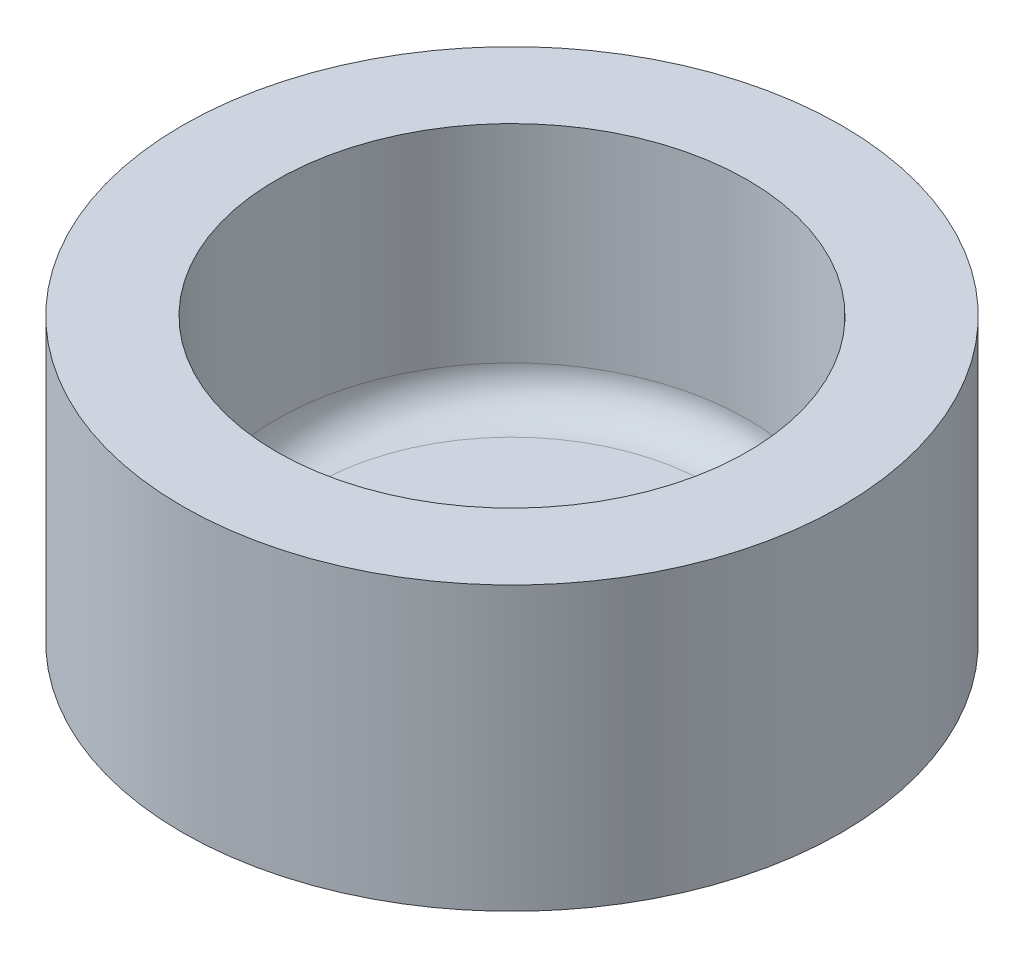
SolidWorks part; units mm, degrees
ref_plane "Front Plane" through (0, 0, 0) normal (0, 0, 1) x (1, 0, 0)
ref_plane "Top Plane" through (0, 0, 0) normal (0, 1, 0) x (1, 0, 0)
ref_plane "Right Plane" through (0, 0, 0) normal (1, 0, 0) x (0, 0, -1)
sketch "Sketch1" plane through (0, 0, 0) normal (0, 1, 0) x (1, 0, 0)
  circle A0 centre (0, 0) radius 17.5
  circle A1 centre (0, 0) radius 12.5
  dimension "D1" = 5
  dimension "D2" = 25
extrude "Boss-Extrude1" add sketch "Sketch1" along normal blind 15
sketch "Sketch2" plane through (0, 0, 0) normal (0, -1, 0) x (1, 0, 0)
  circle A0 centre (0, 0) radius 12.5 construction
  circle A1 centre (0, 0) radius 12.5
extrude "Boss-Extrude2" add sketch "Sketch2" against normal blind 2
fillet "Fillet1" radius 2 1 edges at (0, 2, -12.5)
sketch "Sketch5" plane through (0, 2, 0) normal (0, 1, 0) x (1, 0, 0)
  line L0 (0, 0) -> (0, 24.5) construction
  line L1 (0, 2.5) -> (0, 4.5) construction
  circle A6 centre (0, 0) radius 2.5 construction
  circle A7 centre (0, 0) radius 4.5 construction
  circle A8 centre (0, 0) radius 6.5 construction
  circle A9 centre (0, 0) radius 8.5 construction
  circle A10 centre (0, 0) radius 10.5 construction
  circle A11 centre (0, 0) radius 12.5 construction
  circle A12 centre (0, 0) radius 14.5 construction
  circle A13 centre (0, 0) radius 16.5 construction
  circle A14 centre (0, 0) radius 18.5 construction
  circle A15 centre (0, 0) radius 20.5 construction
  circle A16 centre (0, 0) radius 22.5 construction
  circle A17 centre (0, 0) radius 24.5 construction
  circle A18 centre (0, 2.5) radius 0.5
  circle A20 centre (0, 4.5) radius 0.5
  circle A21 centre (0, 6.5) radius 0.5
  circle A22 centre (0, 8.5) radius 0.5
  circle A23 centre (0, 10.5) radius 0.5
  circle A24 centre (0, 12.5) radius 0.5
  circle A25 centre (0, 14.5) radius 0.5
  circle A26 centre (0, 16.5) radius 0.5
  circle A31 centre (1.7678, 1.7678) radius 0.5
  circle A32 centre (2.5, 0) radius 0.5
  circle A33 centre (1.7678, -1.7678) radius 0.5
  circle A34 centre (0, -2.5) radius 0.5
  circle A35 centre (-1.7678, -1.7678) radius 0.5
  circle A36 centre (-2.5, 0) radius 0.5
  circle A37 centre (-1.7678, 1.7678) radius 0.5
  circle A38 centre (1.9525, 4.0544) radius 0.5
  circle A39 centre (3.5182, 2.8057) radius 0.5
  circle A40 centre (4.3872, 1.0013) radius 0.5
  circle A41 centre (4.3872, -1.0013) radius 0.5
  circle A42 centre (3.5182, -2.8057) radius 0.5
  circle A43 centre (1.9525, -4.0544) radius 0.5
  circle A44 centre (0, -4.5) radius 0.5
  circle A45 centre (-1.9525, -4.0544) radius 0.5
  circle A46 centre (-3.5182, -2.8057) radius 0.5
  circle A47 centre (-4.3872, -1.0013) radius 0.5
  circle A48 centre (-4.3872, 1.0013) radius 0.5
  circle A49 centre (-3.5182, 2.8057) radius 0.5
  circle A50 centre (-1.9525, 4.0544) radius 0.5
  circle A51 centre (1.9159, 6.2112) radius 0.5
  circle A52 centre (3.6616, 5.3706) radius 0.5
  circle A53 centre (5.0819, 4.0527) radius 0.5
  circle A54 centre (6.0507, 2.3747) radius 0.5
  circle A55 centre (6.4818, 0.4857) radius 0.5
  circle A56 centre (6.337, -1.4464) radius 0.5
  circle A57 centre (5.6292, -3.25) radius 0.5
  circle A58 centre (4.4211, -4.7648) radius 0.5
  circle A59 centre (2.8202, -5.8563) radius 0.5
  circle A60 centre (0.9688, -6.4274) radius 0.5
  circle A61 centre (-0.9688, -6.4274) radius 0.5
  circle A62 centre (-2.8202, -5.8563) radius 0.5
  circle A63 centre (-4.4211, -4.7648) radius 0.5
  circle A64 centre (-5.6292, -3.25) radius 0.5
  circle A65 centre (-6.337, -1.4464) radius 0.5
  circle A66 centre (-6.4818, 0.4857) radius 0.5
  circle A67 centre (-6.0507, 2.3747) radius 0.5
  circle A68 centre (-5.0819, 4.0527) radius 0.5
  circle A69 centre (-3.6616, 5.3706) radius 0.5
  circle A70 centre (-1.9159, 6.2112) radius 0.5
  circle A71 centre (1.8914, 8.2869) radius 0.5
  circle A72 centre (3.688, 7.6582) radius 0.5
  circle A73 centre (5.2997, 6.6456) radius 0.5
  circle A74 centre (6.6456, 5.2997) radius 0.5
  circle A75 centre (7.6582, 3.688) radius 0.5
  circle A76 centre (8.2869, 1.8914) radius 0.5
  circle A77 centre (8.5, 0) radius 0.5
  circle A78 centre (8.2869, -1.8914) radius 0.5
  circle A79 centre (7.6582, -3.688) radius 0.5
  circle A80 centre (6.6456, -5.2997) radius 0.5
  circle A81 centre (5.2997, -6.6456) radius 0.5
  circle A82 centre (3.688, -7.6582) radius 0.5
  circle A83 centre (1.8914, -8.2869) radius 0.5
  circle A84 centre (0, -8.5) radius 0.5
  circle A85 centre (-1.8914, -8.2869) radius 0.5
  circle A86 centre (-3.688, -7.6582) radius 0.5
  circle A87 centre (-5.2997, -6.6456) radius 0.5
  circle A88 centre (-6.6456, -5.2997) radius 0.5
  circle A89 centre (-7.6582, -3.688) radius 0.5
  circle A90 centre (-8.2869, -1.8914) radius 0.5
  circle A91 centre (-8.5, 0) radius 0.5
  circle A92 centre (-8.2869, 1.8914) radius 0.5
  circle A93 centre (-7.6582, 3.688) radius 0.5
  circle A94 centre (-6.6456, 5.2997) radius 0.5
  circle A95 centre (-5.2997, 6.6456) radius 0.5
  circle A96 centre (-3.688, 7.6582) radius 0.5
  circle A97 centre (-1.8914, 8.2869) radius 0.5
  circle A98 centre (1.8233, 10.3405) radius 0.5
  circle A99 centre (3.5912, 9.8668) radius 0.5
  circle A100 centre (5.25, 9.0933) radius 0.5
  circle A101 centre (6.7493, 8.0435) radius 0.5
  circle A102 centre (8.0435, 6.7493) radius 0.5
  circle A103 centre (9.0933, 5.25) radius 0.5
  circle A104 centre (9.8668, 3.5912) radius 0.5
  circle A105 centre (10.3405, 1.8233) radius 0.5
  circle A106 centre (10.5, 0) radius 0.5
  circle A107 centre (10.3405, -1.8233) radius 0.5
  circle A108 centre (9.8668, -3.5912) radius 0.5
  circle A109 centre (9.0933, -5.25) radius 0.5
  circle A110 centre (8.0435, -6.7493) radius 0.5
  circle A111 centre (6.7493, -8.0435) radius 0.5
  circle A112 centre (5.25, -9.0933) radius 0.5
  circle A113 centre (3.5912, -9.8668) radius 0.5
  circle A114 centre (1.8233, -10.3405) radius 0.5
  circle A115 centre (0, -10.5) radius 0.5
  circle A116 centre (-1.8233, -10.3405) radius 0.5
  circle A117 centre (-3.5912, -9.8668) radius 0.5
  circle A118 centre (-5.25, -9.0933) radius 0.5
  circle A119 centre (-6.7493, -8.0435) radius 0.5
  circle A120 centre (-8.0435, -6.7493) radius 0.5
  circle A121 centre (-9.0933, -5.25) radius 0.5
  circle A122 centre (-9.8668, -3.5912) radius 0.5
  circle A123 centre (-10.3405, -1.8233) radius 0.5
  circle A124 centre (-10.5, 0) radius 0.5
  circle A125 centre (-10.3405, 1.8233) radius 0.5
  circle A126 centre (-9.8668, 3.5912) radius 0.5
  circle A127 centre (-9.0933, 5.25) radius 0.5
  circle A128 centre (-8.0435, 6.7493) radius 0.5
  circle A129 centre (-6.7493, 8.0435) radius 0.5
  circle A130 centre (-5.25, 9.0933) radius 0.5
  circle A131 centre (-3.5912, 9.8668) radius 0.5
  circle A132 centre (-1.8233, 10.3405) radius 0.5
  circle A133 centre (1.863, 12.3604) radius 0.5
  circle A134 centre (3.6844, 11.9447) radius 0.5
  circle A135 centre (5.4235, 11.2621) radius 0.5
  circle A136 centre (7.0415, 10.328) radius 0.5
  circle A137 centre (8.5022, 9.1631) radius 0.5
  circle A138 centre (9.7729, 7.7936) radius 0.5
  circle A139 centre (10.8253, 6.25) radius 0.5
  circle A140 centre (11.6359, 4.5668) radius 0.5
  circle A141 centre (12.1866, 2.7815) radius 0.5
  circle A142 centre (12.465, 0.9341) radius 0.5
  circle A143 centre (12.465, -0.9341) radius 0.5
  circle A144 centre (12.1866, -2.7815) radius 0.5
  circle A145 centre (11.6359, -4.5668) radius 0.5
  circle A146 centre (10.8253, -6.25) radius 0.5
  circle A147 centre (9.7729, -7.7936) radius 0.5
  circle A148 centre (8.5022, -9.1631) radius 0.5
  circle A149 centre (7.0415, -10.328) radius 0.5
  circle A150 centre (5.4235, -11.2621) radius 0.5
  circle A151 centre (3.6844, -11.9447) radius 0.5
  circle A152 centre (1.863, -12.3604) radius 0.5
  circle A153 centre (0, -12.5) radius 0.5
  circle A154 centre (-1.863, -12.3604) radius 0.5
  circle A155 centre (-3.6844, -11.9447) radius 0.5
  circle A156 centre (-5.4235, -11.2621) radius 0.5
  circle A157 centre (-7.0415, -10.328) radius 0.5
  circle A158 centre (-8.5022, -9.1631) radius 0.5
  circle A159 centre (-9.7729, -7.7936) radius 0.5
  circle A160 centre (-10.8253, -6.25) radius 0.5
  circle A161 centre (-11.6359, -4.5668) radius 0.5
  circle A162 centre (-12.1866, -2.7815) radius 0.5
  circle A163 centre (-12.465, -0.9341) radius 0.5
  circle A164 centre (-12.465, 0.9341) radius 0.5
  circle A165 centre (-12.1866, 2.7815) radius 0.5
  circle A166 centre (-11.6359, 4.5668) radius 0.5
  circle A167 centre (-10.8253, 6.25) radius 0.5
  circle A168 centre (-9.7729, 7.7936) radius 0.5
  circle A169 centre (-8.5022, 9.1631) radius 0.5
  circle A170 centre (-7.0415, 10.328) radius 0.5
  circle A171 centre (-5.4235, 11.2621) radius 0.5
  circle A172 centre (-3.6844, 11.9447) radius 0.5
  circle A173 centre (-1.863, 12.3604) radius 0.5
  circle A174 centre (1.8542, 14.381) radius 0.5
  circle A175 centre (3.678, 14.0258) radius 0.5
  circle A176 centre (5.4414, 13.4403) radius 0.5
  circle A177 centre (7.1154, 12.6341) radius 0.5
  circle A178 centre (8.6726, 11.6205) radius 0.5
  circle A179 centre (10.0874, 10.4161) radius 0.5
  circle A180 centre (11.3366, 9.0406) radius 0.5
  circle A181 centre (12.3996, 7.5167) radius 0.5
  circle A182 centre (13.259, 5.8694) radius 0.5
  circle A183 centre (13.9007, 4.1257) radius 0.5
  circle A184 centre (14.3141, 2.3142) radius 0.5
  circle A185 centre (14.4926, 0.4647) radius 0.5
  circle A186 centre (14.433, -1.3923) radius 0.5
  circle A187 centre (14.1365, -3.2266) radius 0.5
  circle A188 centre (13.6078, -5.0078) radius 0.5
  circle A189 centre (12.8557, -6.7068) radius 0.5
  circle A190 centre (11.8925, -8.2957) radius 0.5
  circle A191 centre (10.734, -9.7484) radius 0.5
  circle A192 centre (9.3993, -11.041) radius 0.5
  circle A193 centre (7.9103, -12.1523) radius 0.5
  circle A194 centre (6.2913, -13.064) radius 0.5
  circle A195 centre (4.5691, -13.7613) radius 0.5
  circle A196 centre (2.7718, -14.2326) radius 0.5
  circle A197 centre (0.929, -14.4702) radius 0.5
  circle A198 centre (-0.929, -14.4702) radius 0.5
  circle A199 centre (-2.7718, -14.2326) radius 0.5
  circle A200 centre (-4.5691, -13.7613) radius 0.5
  circle A201 centre (-6.2913, -13.064) radius 0.5
  circle A202 centre (-7.9103, -12.1523) radius 0.5
  circle A203 centre (-9.3993, -11.041) radius 0.5
  circle A204 centre (-10.734, -9.7484) radius 0.5
  circle A205 centre (-11.8925, -8.2957) radius 0.5
  circle A206 centre (-12.8557, -6.7068) radius 0.5
  circle A207 centre (-13.6078, -5.0078) radius 0.5
  circle A208 centre (-14.1365, -3.2266) radius 0.5
  circle A209 centre (-14.433, -1.3923) radius 0.5
  circle A210 centre (-14.4926, 0.4647) radius 0.5
  circle A211 centre (-14.3141, 2.3142) radius 0.5
  circle A212 centre (-13.9007, 4.1257) radius 0.5
  circle A213 centre (-13.259, 5.8694) radius 0.5
  circle A214 centre (-12.3996, 7.5167) radius 0.5
  circle A215 centre (-11.3366, 9.0406) radius 0.5
  circle A216 centre (-10.0874, 10.4161) radius 0.5
  circle A217 centre (-8.6726, 11.6205) radius 0.5
  circle A218 centre (-7.1154, 12.6341) radius 0.5
  circle A219 centre (-5.4414, 13.4403) radius 0.5
  circle A220 centre (-3.678, 14.0258) radius 0.5
  circle A221 centre (-1.8542, 14.381) radius 0.5
  circle A222 centre (1.8809, 16.3924) radius 0.5
  circle A223 centre (3.7372, 16.0712) radius 0.5
  circle A224 centre (5.5448, 15.5404) radius 0.5
  circle A225 centre (7.2801, 14.8071) radius 0.5
  circle A226 centre (8.9206, 13.8807) radius 0.5
  circle A227 centre (10.4447, 12.7733) radius 0.5
  circle A228 centre (11.8327, 11.4995) radius 0.5
  circle A229 centre (13.0664, 10.0757) radius 0.5
  circle A230 centre (14.1298, 8.5206) radius 0.5
  circle A231 centre (15.0089, 6.8543) radius 0.5
  circle A232 centre (15.6924, 5.0988) radius 0.5
  circle A233 centre (16.1714, 3.2767) radius 0.5
  circle A234 centre (16.4395, 1.412) radius 0.5
  circle A235 centre (16.4933, -0.4712) radius 0.5
  circle A236 centre (16.3321, -2.3482) radius 0.5
  circle A237 centre (15.9579, -4.1946) radius 0.5
  circle A238 centre (15.3758, -5.9863) radius 0.5
  circle A239 centre (14.5931, -7.7) radius 0.5
  circle A240 centre (13.6203, -9.3133) radius 0.5
  circle A241 centre (12.4699, -10.8052) radius 0.5
  circle A242 centre (11.1569, -12.1562) radius 0.5
  circle A243 centre (9.6985, -13.3488) radius 0.5
  circle A244 centre (8.1136, -14.3673) radius 0.5
  circle A245 centre (6.423, -15.1985) radius 0.5
  circle A246 centre (4.6486, -15.8316) radius 0.5
  circle A247 centre (2.8136, -16.2583) radius 0.5
  circle A248 centre (0.942, -16.4731) radius 0.5
  circle A249 centre (-0.942, -16.4731) radius 0.5
  circle A250 centre (-2.8136, -16.2583) radius 0.5
  circle A251 centre (-4.6486, -15.8316) radius 0.5
  circle A252 centre (-6.423, -15.1985) radius 0.5
  circle A253 centre (-8.1136, -14.3673) radius 0.5
  circle A254 centre (-9.6985, -13.3488) radius 0.5
  circle A255 centre (-11.1569, -12.1562) radius 0.5
  circle A256 centre (-12.4699, -10.8052) radius 0.5
  circle A257 centre (-13.6203, -9.3133) radius 0.5
  circle A258 centre (-14.5931, -7.7) radius 0.5
  circle A259 centre (-15.3758, -5.9863) radius 0.5
  circle A260 centre (-15.9579, -4.1946) radius 0.5
  circle A261 centre (-16.3321, -2.3482) radius 0.5
  circle A262 centre (-16.4933, -0.4712) radius 0.5
  circle A263 centre (-16.4395, 1.412) radius 0.5
  circle A264 centre (-16.1714, 3.2767) radius 0.5
  circle A265 centre (-15.6924, 5.0988) radius 0.5
  circle A266 centre (-15.0089, 6.8543) radius 0.5
  circle A267 centre (-14.1298, 8.5206) radius 0.5
  circle A268 centre (-13.0664, 10.0757) radius 0.5
  circle A269 centre (-11.8327, 11.4995) radius 0.5
  circle A270 centre (-10.4447, 12.7733) radius 0.5
  circle A271 centre (-8.9206, 13.8807) radius 0.5
  circle A272 centre (-7.2801, 14.8071) radius 0.5
  circle A273 centre (-5.5448, 15.5404) radius 0.5
  circle A274 centre (-3.7372, 16.0712) radius 0.5
  circle A275 centre (-1.8809, 16.3924) radius 0.5
  circle A276 centre (0, 18.5) radius 0.5 [skipped]
  circle A277 centre (0, 20.5) radius 0.5 [skipped]
  circle A278 centre (0, 22.5) radius 0.5 [skipped]
  circle A279 centre (0, 24.5) radius 0.5 [skipped]
  point P69 (0, 0)
  point P95 (0, 0)
  point P137 (0, 0)
  point P192 (0, 0)
  point P263 (0, 0)
  point P346 (0, 0)
  point P443 (0, 0)
  point P552 (0, 0)
  dimension "D1" = 5
  dimension "D13" = 1
  dimension "D14" = 2
  dimension "D2" = 2
  dimension "D3" = 2
  dimension "D4" = 2
  dimension "D5" = 2
  dimension "D6" = 2
  dimension "D7" = 2
  dimension "D8" = 2
  dimension "D9" = 2
  dimension "D10" = 2
  dimension "D11" = 2
  dimension "D12" = 2
  dimension "D15" = 12
  dimension "D16" = 8
  dimension "D17" = 14
  dimension "D18" = 21
  dimension "D19" = 28
  dimension "D20" = 36
  dimension "D21" = 42
  dimension "D22" = 49
  dimension "D23" = 55
extrude "Cut-Extrude1" [suppressed] cut sketch "Sketch5" against normal up to next
sketch "Sketch6" plane through (0, 2, 0) normal (0, 1, 0) x (1, 0, 0)
  line L1 (-5, -5) -> (5, -5) construction
  line L2 (-5, -5) -> (-5, 5) construction
  line L3 (-5, 5) -> (5, 5) construction
  line L4 (5, -5) -> (5, 5) construction
  line L5 (-5, -5) -> (5, 5) construction
  line L6 (-5, 5) -> (5, -5) construction
  circle A0 centre (5, 5) radius 1
  circle A1 centre (-5, 5) radius 1
  circle A2 centre (-5, -5) radius 2
  circle A3 centre (5, -5) radius 2.5
  circle A4 centre (0, 0) radius 1.5
  point P0 (0, 0)
  dimension "D1" = 2
  dimension "D2" = 2
  dimension "D3" = 5
  dimension "D4" = 4
  dimension "D5" = 3
  dimension "D6" = 10
  dimension "D7" = 10
extrude "Cut-Extrude2" [suppressed] cut sketch "Sketch6" against normal up to next
